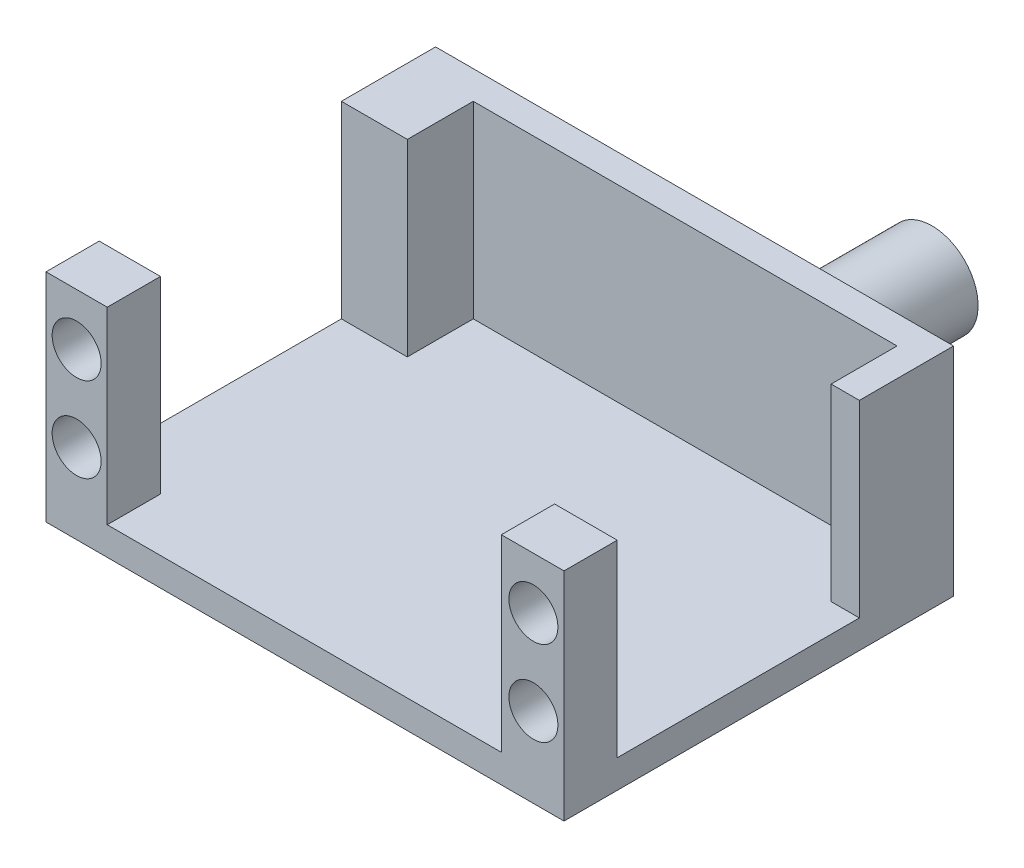
SolidWorks part; units mm, degrees
ref_plane "Front Plane" through (0, 0, 0) normal (0, 0, 1) x (1, 0, 0)
ref_plane "Top Plane" through (0, 0, 0) normal (0, 1, 0) x (1, 0, 0)
ref_plane "Right Plane" through (0, 0, 0) normal (1, 0, 0) x (0, 0, -1)
sketch "Sketch1" plane through (0, 0, 0) normal (0, 1, 0) x (1, 0, 0)
  line L1 (-20.675, -14.175) -> (20.675, -14.175) construction
  line L2 (-20.675, -14.175) -> (-20.675, 14.175) construction
  line L3 (-20.675, 14.175) -> (20.675, 14.175) construction
  line L4 (20.675, -14.175) -> (20.675, 14.175) construction
  line L5 (-20.675, -14.175) -> (20.675, 14.175) construction
  line L6 (-20.675, 14.175) -> (20.675, -14.175) construction
  line L11 (-27.49, -23.675) -> (27.49, -23.675)
  line L12 (-27.49, -23.675) -> (-27.49, 17.675)
  line L13 (-27.49, 17.675) -> (27.49, 17.675)
  line L14 (27.49, -23.675) -> (27.49, 17.675)
  point P0 (0, 0)
  point P6 (0, 0)
  dimension "D1" = 41.35
  dimension "D2" = 28.35
  dimension "D3" = 6.815
  dimension "D4" = 3.5
  dimension "D5" = 9.5
  dimension "D6" = 6.815
extrude "Boss-Extrude1" add sketch "Sketch1" along normal blind 3
sketch "Sketch2" plane through (0, 3, 0) normal (0, 1, 0) x (1, 0, 0)
  line L0 (27.49, -23.675) -> (27.49, 17.675) construction
  line L1 (-27.49, -23.675) -> (-20.99, -23.675)
  line L2 (-27.49, -23.675) -> (-27.49, -18.025)
  line L3 (-27.49, -18.025) -> (-20.99, -18.025)
  line L4 (-20.99, -23.675) -> (-20.99, -18.025)
  line L5 (27.49, -23.675) -> (20.84, -23.675)
  line L6 (27.49, -23.675) -> (27.49, -18.025)
  line L7 (27.49, -18.025) -> (20.84, -18.025)
  line L8 (20.84, -23.675) -> (20.84, -18.025)
  line L9 (-27.49, 17.675) -> (27.49, 17.675)
  line L11 (-20.49, 14.675) -> (24.49, 14.675)
  line L13 (-27.49, 17.675) -> (-27.49, -23.675) construction
  line L22 (-27.49, 7.675) -> (-20.49, 7.675)
  line L23 (-27.49, 7.675) -> (-27.49, 17.675)
  line L25 (-20.49, 7.675) -> (-20.49, 14.675)
  line L28 (27.49, 17.675) -> (27.49, 7.675)
  line L29 (27.49, 7.675) -> (24.49, 7.675)
  line L30 (24.49, 14.675) -> (24.49, 7.675)
  dimension "D1" = 5.65
  dimension "D2" = 6.5
  dimension "D3" = 5.65
  dimension "D4" = 6.65
  dimension "D6" = 7
  dimension "D7" = 7
  dimension "D8" = 3
  dimension "D9" = 7
  dimension "D10" = 3
extrude "Boss-Extrude2" add sketch "Sketch2" along normal blind 20
sketch "Sketch3" plane through (0, 0, -17.675) normal (0, 0, -1) x (-1, 0, 0)
  line L1 (-27.49, 23) -> (-27.49, 0) construction
  line L2 (-27.49, 0) -> (27.49, 0) construction
  circle A0 centre (-10.19, 13) radius 4.9
  dimension "D2" = 9.8
  dimension "D1" = 17.3
  dimension "D3" = 13
extrude "Boss-Extrude3" add sketch "Sketch3" along normal blind 15
sketch "Sketch4" plane through (0, 0, 23.675) normal (0, 0, 1) x (1, 0, 0)
  line L0 (-27.49, 23) -> (-20.99, 23) construction
  line L1 (-27.49, 23) -> (-27.49, 0) construction
  line L3 (27.49, 23) -> (27.49, 0) construction
  circle A0 centre (-24.24, 17.5) radius 2.6
  circle A1 centre (-24.24, 8.5) radius 2.6
  circle A2 centre (24.24, 17.5) radius 2.6
  circle A3 centre (24.24, 8.5) radius 2.6
  dimension "D1" = 5.2
  dimension "D2" = 5.2
  dimension "D3" = 5.2
  dimension "D4" = 5.2
  dimension "D5" = 9
  dimension "D6" = 5.5
  dimension "D7" = 3.25
  dimension "D8" = 3.25
extrude "Cut-Extrude1" cut sketch "Sketch4" against normal up to next
